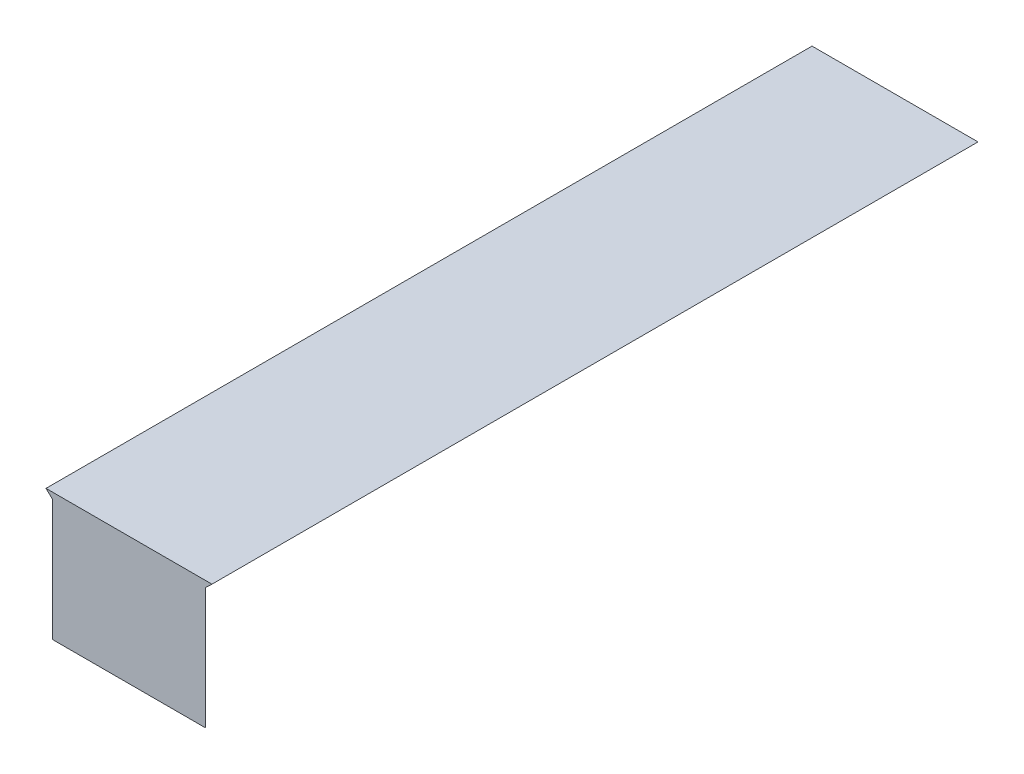
SolidWorks part; units mm, degrees
ref_plane "Front Plane" through (0, 0, 0) normal (0, 0, 1) x (1, 0, 0)
ref_plane "Top Plane" through (0, 0, 0) normal (0, 1, 0) x (1, 0, 0)
ref_plane "Right Plane" through (0, 0, 0) normal (1, 0, 0) x (0, 0, -1)
sketch "Sketch1" plane through (0, 0, 0) normal (0, 0, 1) x (1, 0, 0)
  line L0 (-300, 100) -> (300, 100) construction
  line L1 (-65, 100) -> (-60, 95.25) construction
  line L2 (-60, 95.25) -> (-45, 81) construction
  line L3 (60, 95.25) -> (65, 100) construction
  line L4 (45, 81) -> (60, 95.25) construction
  line L5 (45, 81) -> (-45, 81) construction
  line L6 (-65, 100) -> (65, 100)
  line L7 (-65, 100) -> (-60, 95.25)
  line L8 (-60, 95.25) -> (-45, 81)
  line L9 (60, 95.25) -> (65, 100)
  line L10 (45, 81) -> (60, 95.25)
  line L11 (45, 81) -> (-45, 81)
extrude "Boss-Extrude1" add sketch "Sketch1" against normal up to surface (600 mm away)
sketch "Sketch2" plane through (0, 0, 0) normal (0, -1, 0) x (1, 0, 0)
  line L0 (-45, -15) -> (-60, 0) construction
  line L1 (45, -15) -> (-45, -15) construction
  line L2 (60, 0) -> (45, -15) construction
  line L3 (-45, -15) -> (-60, 0)
  line L4 (45, -15) -> (-45, -15)
  line L5 (60, 0) -> (45, -15)
  line L6 (60, 0) -> (-60, 0)
extrude "Boss-Extrude2" add sketch "Sketch2" against normal up to vertex (100 mm away)
